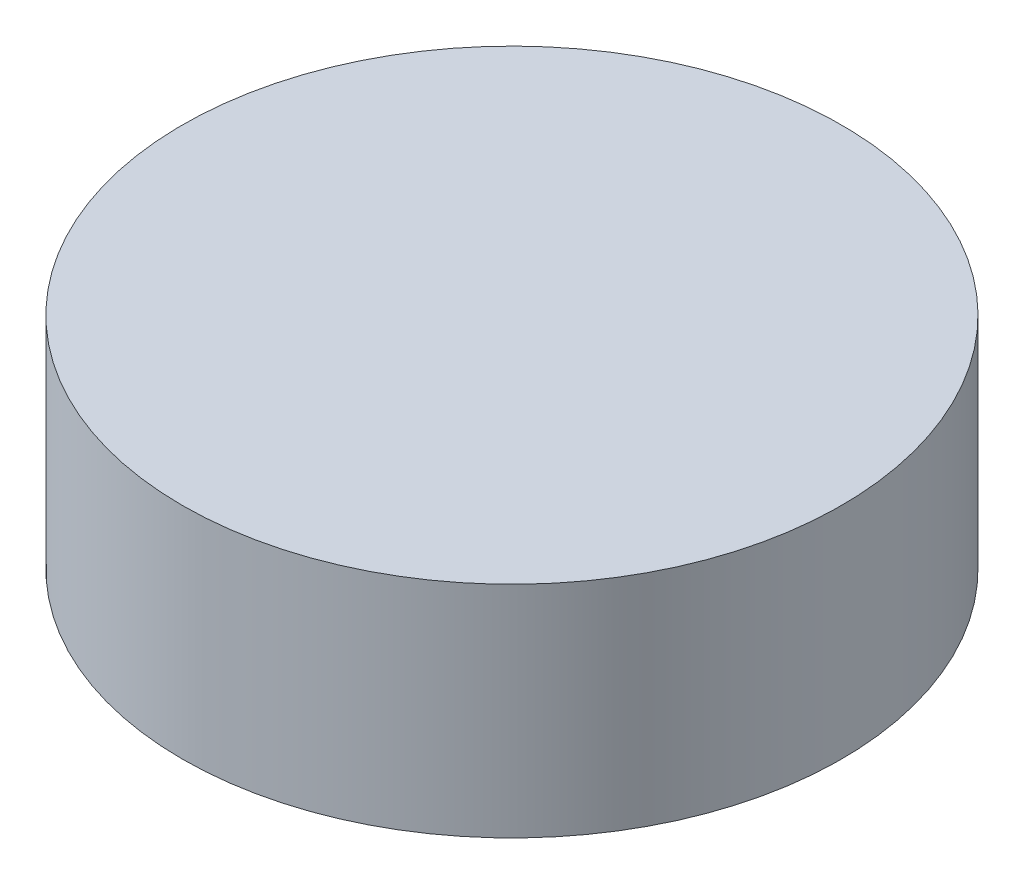
SolidWorks part; units mm, degrees
material "Stainless Steel (ferritic)"
ref_plane "Front Plane" through (0, 0, 0) normal (0, 0, 1) x (1, 0, 0)
ref_plane "Top Plane" through (0, 0, 0) normal (0, 1, 0) x (1, 0, 0)
ref_plane "Right Plane" through (0, 0, 0) normal (1, 0, 0) x (0, 0, -1)
sketch "Sketch1" plane through (0, 0, 0) normal (0, 1, 0) x (1, 0, 0)
  circle A0 centre (0, 0) radius 3
extrude "Boss-Extrude1" add sketch "Sketch1" along normal blind 2
